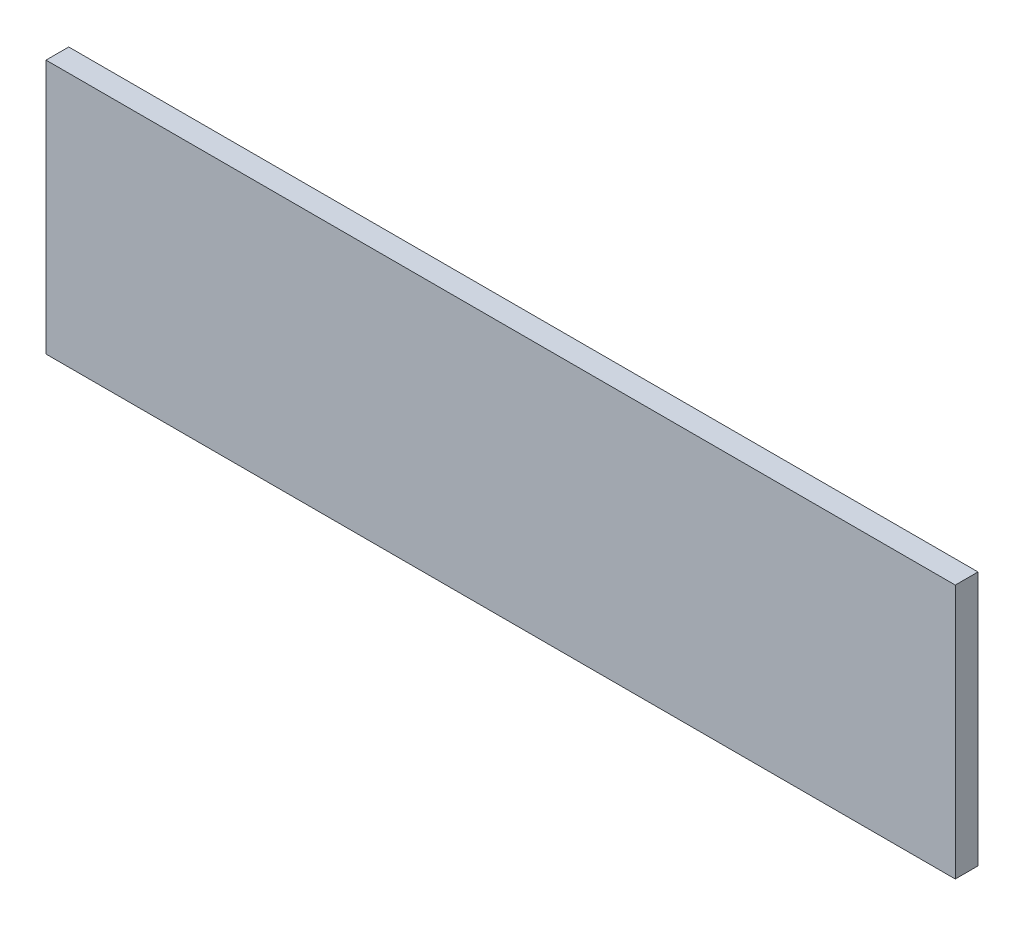
SolidWorks part; units mm, degrees
ref_plane "Front Plane" through (0, 0, 0) normal (0, 0, 1) x (1, 0, 0)
ref_plane "Top Plane" through (0, 0, 0) normal (0, 1, 0) x (1, 0, 0)
ref_plane "Right Plane" through (0, 0, 0) normal (1, 0, 0) x (0, 0, -1)
sketch "Sketch1" plane through (0, 0, 0) normal (0, 0, 1) x (1, 0, 0)
  line L1 (0, 0) -> (127, 0)
  line L2 (0, 0) -> (0, 35.56)
  line L3 (0, 35.56) -> (127, 35.56)
  line L4 (127, 0) -> (127, 35.56)
  dimension "D1" = 127
  dimension "D2" = 35.56
extrude "Boss-Extrude1" add sketch "Sketch1" along normal blind 3.175
